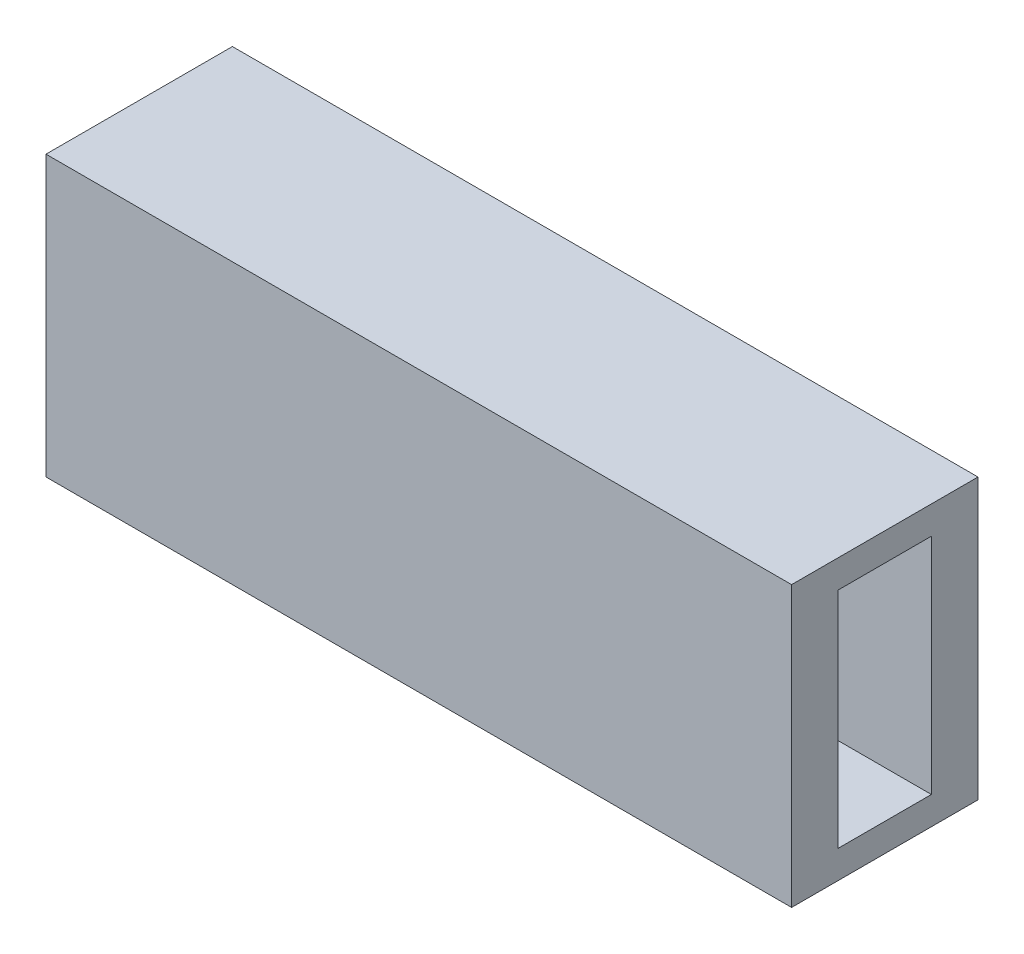
SolidWorks part; units mm, degrees
material "Copper"
ref_plane "Front Plane" through (0, 0, 0) normal (0, 0, 1) x (1, 0, 0)
ref_plane "Top Plane" through (0, 0, 0) normal (0, 1, 0) x (1, 0, 0)
ref_plane "Right Plane" through (0, 0, 0) normal (1, 0, 0) x (0, 0, -1)
sketch "Sketch1" plane through (0, 0, 0) normal (1, 0, 0) x (0, 0, -1)
  line L1 (7.5, -18) -> (-7.5, -18)
  line L2 (7.5, -18) -> (7.5, 18)
  line L3 (7.5, 18) -> (-7.5, 18)
  line L4 (-7.5, -18) -> (-7.5, 18)
  line L5 (7.5, -18) -> (-7.5, 18) construction
  line L6 (7.5, 18) -> (-7.5, -18) construction
  line L7 (15, -22.5) -> (-15, -22.5)
  line L8 (15, -22.5) -> (15, 22.5)
  line L9 (15, 22.5) -> (-15, 22.5)
  line L10 (-15, -22.5) -> (-15, 22.5)
  line L11 (15, -22.5) -> (-15, 22.5) construction
  line L12 (15, 22.5) -> (-15, -22.5) construction
  point P0 (0, 0)
  point P6 (0, 0)
  dimension "D1" = 15
  dimension "D2" = 36
  dimension "D3" = 45
  dimension "D4" = 30
extrude "Boss-Extrude1" add sketch "Sketch1" along normal mid plane 120
